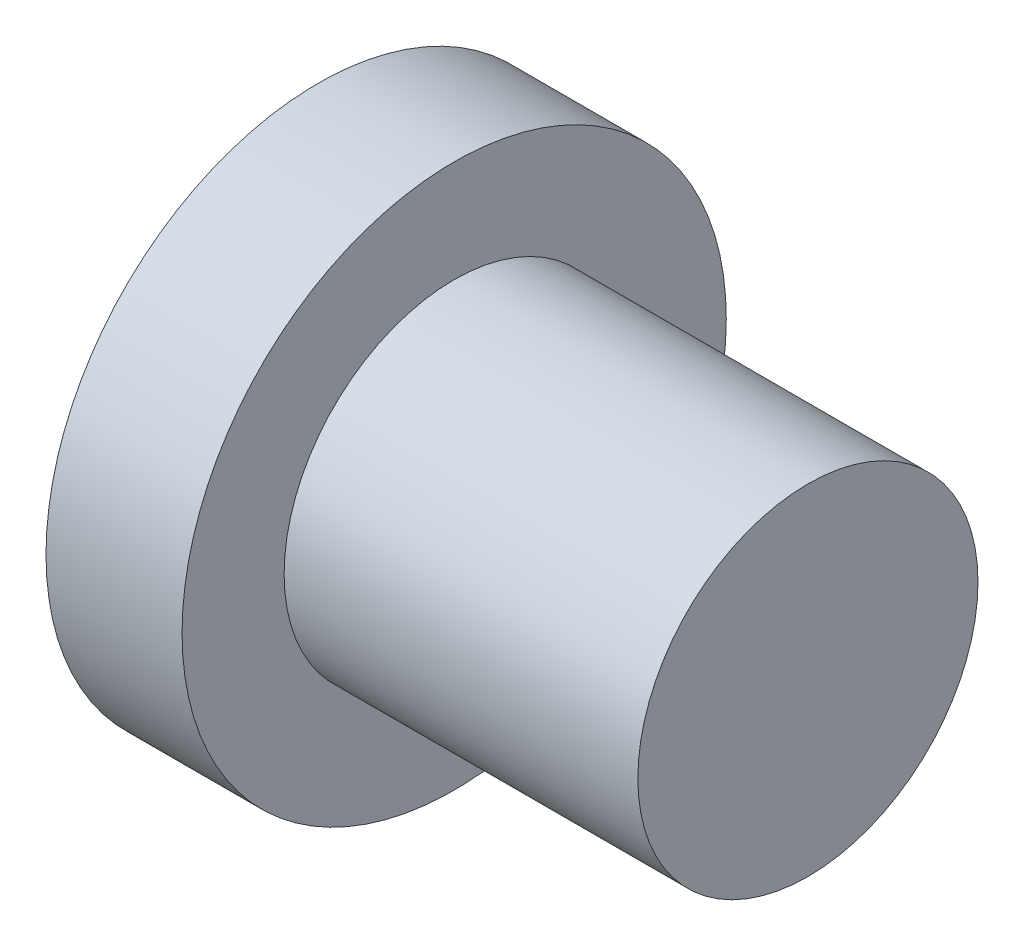
SolidWorks part; units mm, degrees
material "1060 Alloy"
ref_plane "Front Plane" through (0, 0, 0) normal (0, 0, 1) x (1, 0, 0)
ref_plane "Top Plane" through (0, 0, 0) normal (0, 1, 0) x (1, 0, 0)
ref_plane "Right Plane" through (0, 0, 0) normal (1, 0, 0) x (0, 0, -1)
sketch "Sketch1" plane through (0, 0, 0) normal (1, 0, 0) x (0, 0, -1)
  circle A0 centre (0, 0) radius 20
  dimension "D1" = 40
extrude "Boss-Extrude1" add sketch "Sketch1" along normal blind 10
sketch "Sketch2" plane through (10, 0, 0) normal (1, 0, 0) x (0, 0, -1)
  circle A0 centre (0, 0) radius 12.5
  dimension "D1" = 25
extrude "Boss-Extrude2" add sketch "Sketch2" along normal blind 26
